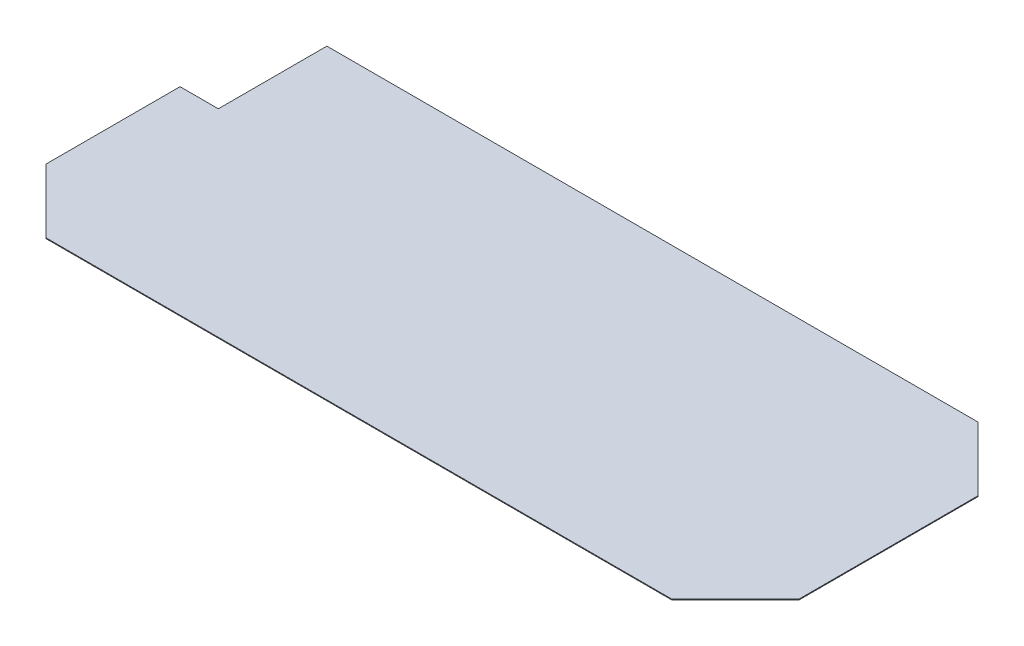
SolidWorks part; units mm, degrees
material "PMMA"
ref_plane "Front Plane" through (0, 0, 0) normal (0, 0, 1) x (1, 0, 0)
ref_plane "Top Plane" through (0, 0, 0) normal (0, 1, 0) x (1, 0, 0)
ref_plane "Right Plane" through (0, 0, 0) normal (1, 0, 0) x (0, 0, -1)
sketch "Sketch1" plane through (0, 0, 0) normal (0, 1, 0) x (1, 0, 0)
  line L0 (1498.6, 127) -> (1371.6, 0)
  line L1 (127, 0) -> (1371.6, 0)
  line L2 (0, 127) -> (0, 393.7)
  line L3 (76.2, 609.6) -> (1371.6, 609.6)
  line L4 (1498.6, 127) -> (1498.6, 482.6)
  line L5 (1498.6, 482.6) -> (1371.6, 609.6)
  line L6 (127, 0) -> (0, 127)
  line L7 (0, 393.7) -> (76.2, 393.7)
  line L8 (76.2, 609.6) -> (76.2, 393.7)
  dimension "D2" = 609.6
  dimension "D3" = 215.9
  dimension "D4" = 76.2
  dimension "D5" = 1498.6
extrude "Boss-Extrude1" add sketch "Sketch1" along normal blind 1.5875
